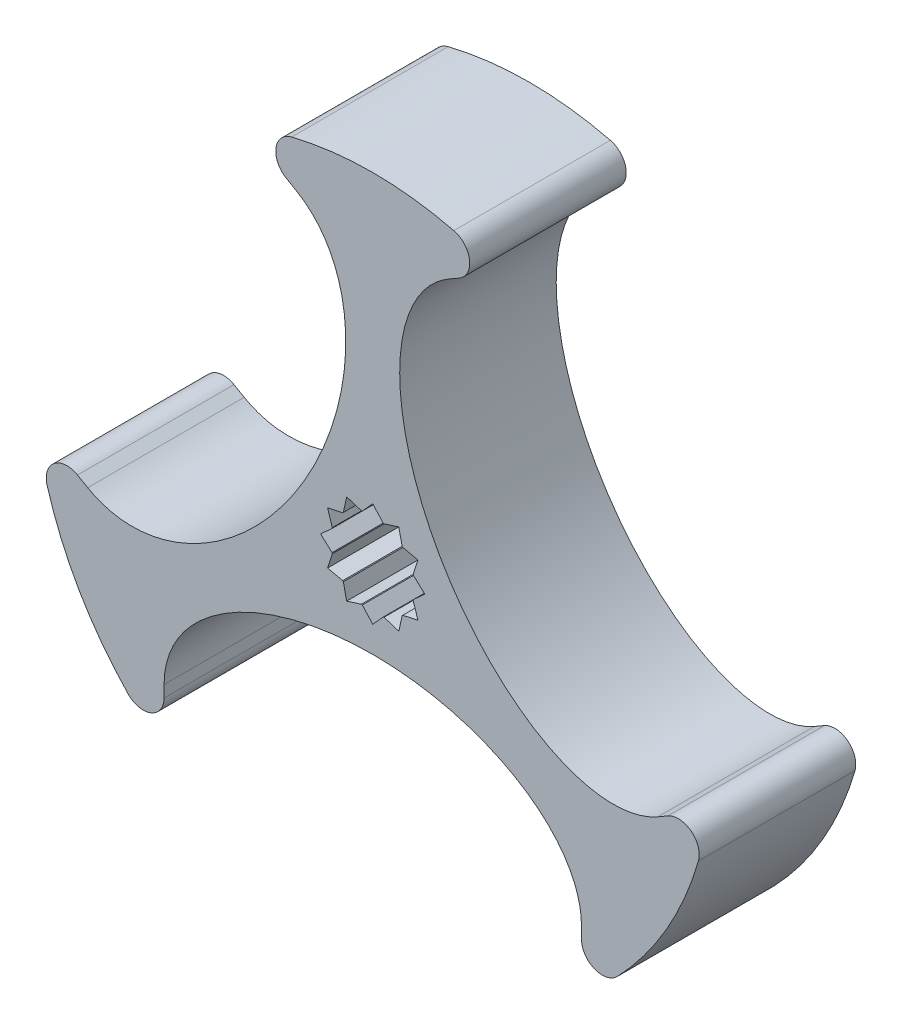
SolidWorks part; units mm, degrees
ref_plane "Alzado" through (0, 0, 0) normal (0, 0, 1) x (1, 0, 0)
ref_plane "Planta" through (0, 0, 0) normal (0, 1, 0) x (1, 0, 0)
ref_plane "Vista lateral" through (0, 0, 0) normal (1, 0, 0) x (0, 0, -1)
sketch "Croquis1" plane through (0, 0, 0) normal (0, 0, 1) x (1, 0, 0)
  line L0 (20, -20) -> (20, -21.1246)
  line L1 (-20, -20) -> (-20, -21.1246)
  line L2 (-27.3205, -7.3205) -> (-28.2945, -6.7582)
  line L3 (-7.3205, 27.3205) -> (-8.2945, 27.8828)
  line L4 (7.3205, 27.3205) -> (8.2945, 27.8828)
  line L5 (27.3205, -7.3205) -> (28.2945, -6.7582)
  circle A2 centre (0, 0) radius 28.2843 construction
  arc A3 (23.4426, -22.5099) -> (31.2154, -9.047) centre (0, 0) ccw
  arc A4 (-31.2154, -9.047) -> (-23.4426, -22.5099) centre (0, 0) ccw
  arc A5 (7.7728, 31.5568) -> (-7.7728, 31.5568) centre (0, 0) ccw
  arc A6 (-7.7728, 31.5568) -> (-8.2945, 27.8828) centre (-7.2945, 29.6149) ccw
  arc A7 (7.7728, 31.5568) -> (8.2945, 27.8828) centre (7.2945, 29.6149) cw
  arc A8 (31.2154, -9.047) -> (28.2945, -6.7582) centre (29.2945, -8.4902) ccw
  arc A9 (23.4426, -22.5099) -> (20, -21.1246) centre (22, -21.1246) cw
  arc A10 (-20, -21.1246) -> (-23.4426, -22.5099) centre (-22, -21.1246) cw
  arc A11 (-31.2154, -9.047) -> (-28.2945, -6.7582) centre (-29.2945, -8.4902) cw
  ellipse E0 centre (0, -20) end of major axis (-20, -20) minor radius 12.5 (20, -20) -> (-20, -20) ccw
  ellipse E1 centre (-17.3205, 10) end of major axis (-27.3205, -7.3205) minor radius 12.5 (-27.3205, -7.3205) -> (-7.3205, 27.3205) ccw
  ellipse E2 centre (17.3205, 10) end of major axis (27.3205, -7.3205) minor radius 12.5 (7.3205, 27.3205) -> (27.3205, -7.3205) ccw
  point P24 (0, 0)
  point P38 (0, 0)
  dimension "D2" = 2
  dimension "D6" = 32.5
  dimension "D1" = 40
  dimension "D3" = 20
  dimension "D4" = 3
  dimension "D5" = 3
extrude "Saliente-Extruir2" add sketch "Croquis1" along normal blind 15
sketch "Croquis2" plane through (0, 0, 15) normal (0, 0, 1) x (1, 0, 0)
  circle A0 centre (0, 0) radius 4.025
  dimension "D1" = 8.05
extrude "Cortar-Extruir1" cut sketch "Croquis2" against normal through all
sketch "Croquis3" plane through (0, 0, 15) normal (0, 0, 1) x (1, 0, 0)
  line L0 (-1, 3.8988) -> (0, 5)
  line L1 (0, 5) -> (1, 3.8988)
  line L2 (1, 3.8988) -> (-1, 3.8988)
  line L3 (1.0834, 3.8765) -> (2.5, 4.3301)
  line L4 (2.5, 4.3301) -> (2.8154, 2.8765)
  line L5 (2.8154, 2.8765) -> (1.0834, 3.8765)
  line L6 (2.8765, 2.8154) -> (4.3301, 2.5)
  line L7 (4.3301, 2.5) -> (3.8765, 1.0834)
  line L8 (3.8765, 1.0834) -> (2.8765, 2.8154)
  line L9 (3.8988, 1) -> (5, 0)
  line L10 (5, 0) -> (3.8988, -1)
  line L11 (3.8988, -1) -> (3.8988, 1)
  line L12 (3.8765, -1.0834) -> (4.3301, -2.5)
  line L13 (4.3301, -2.5) -> (2.8765, -2.8154)
  line L14 (2.8765, -2.8154) -> (3.8765, -1.0834)
  line L15 (2.8154, -2.8765) -> (2.5, -4.3301)
  line L16 (2.5, -4.3301) -> (1.0834, -3.8765)
  line L17 (1.0834, -3.8765) -> (2.8154, -2.8765)
  line L18 (1, -3.8988) -> (0, -5)
  line L19 (0, -5) -> (-1, -3.8988)
  line L20 (-1, -3.8988) -> (1, -3.8988)
  line L21 (-1.0834, -3.8765) -> (-2.5, -4.3301)
  line L22 (-2.5, -4.3301) -> (-2.8154, -2.8765)
  line L23 (-2.8154, -2.8765) -> (-1.0834, -3.8765)
  line L24 (-2.8765, -2.8154) -> (-4.3301, -2.5)
  line L25 (-4.3301, -2.5) -> (-3.8765, -1.0834)
  line L26 (-3.8765, -1.0834) -> (-2.8765, -2.8154)
  line L27 (-3.8988, -1) -> (-5, 0)
  line L28 (-5, 0) -> (-3.8988, 1)
  line L29 (-3.8988, 1) -> (-3.8988, -1)
  line L30 (-3.8765, 1.0834) -> (-4.3301, 2.5)
  line L31 (-4.3301, 2.5) -> (-2.8765, 2.8154)
  line L32 (-2.8765, 2.8154) -> (-3.8765, 1.0834)
  line L33 (-2.8154, 2.8765) -> (-2.5, 4.3301)
  line L34 (-2.5, 4.3301) -> (-1.0834, 3.8765)
  line L35 (-1.0834, 3.8765) -> (-2.8154, 2.8765)
  circle A1 centre (0, 0) radius 4.025 construction
  point P42 (0, 0)
  dimension "D1" = 5
  dimension "D2" = 2
  dimension "D3" = 12
extrude "Cortar-Extruir2" cut sketch "Croquis3" against normal through all
